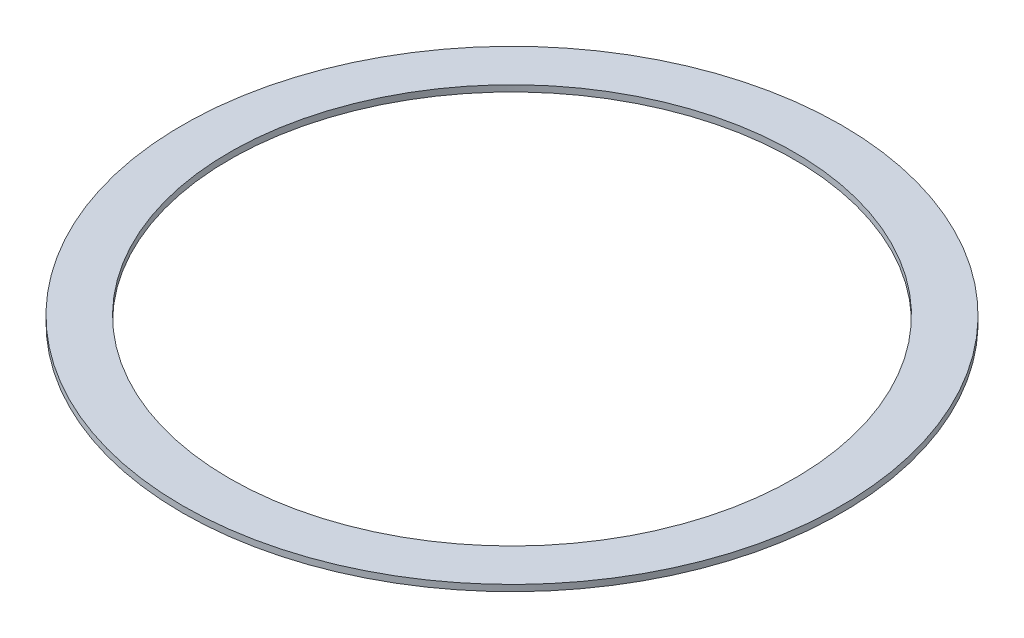
SolidWorks part; units mm, degrees
ref_plane "Plano frontal" through (0, 0, 0) normal (0, 0, 1) x (1, 0, 0)
ref_plane "Plano superior" through (0, 0, 0) normal (0, 1, 0) x (1, 0, 0)
ref_plane "Plano direito" through (0, 0, 0) normal (1, 0, 0) x (0, 0, -1)
sketch "Esboço1" plane through (0, 0, 0) normal (0, 1, 0) x (1, 0, 0)
  circle A0 centre (0, 0) radius 52.5
  circle A1 centre (0, 0) radius 45
  dimension "D1" = 105
  dimension "D2" = 90
extrude "Ressalto-extrusão1" add sketch "Esboço1" along normal blind 1
